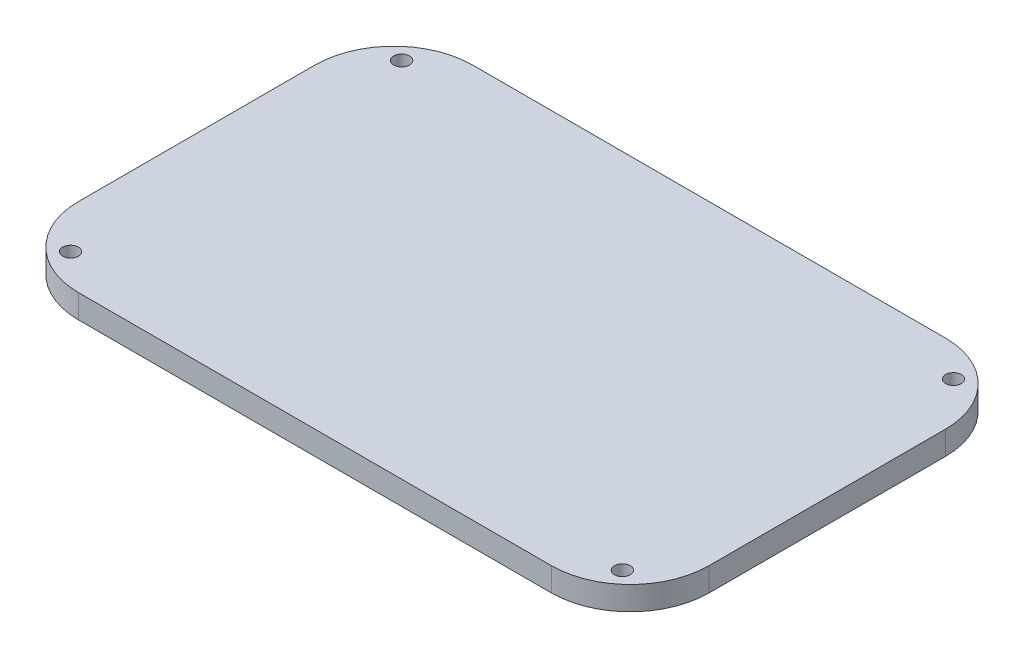
SolidWorks part; units mm, degrees
ref_plane "Front Plane" through (0, 0, 0) normal (0, 0, 1) x (1, 0, 0)
ref_plane "Top Plane" through (0, 0, 0) normal (0, 1, 0) x (1, 0, 0)
ref_plane "Right Plane" through (0, 0, 0) normal (1, 0, 0) x (0, 0, -1)
sketch "Sketch1" plane through (0, 0, 0) normal (0, 1, 0) x (1, 0, 0)
  line L1 (40, 25) -> (-40, 25)
  line L2 (40, 25) -> (40, -25)
  line L3 (40, -25) -> (-40, -25)
  line L4 (-40, 25) -> (-40, -25)
  line L5 (40, 25) -> (-40, -25) construction
  line L6 (40, -25) -> (-40, 25) construction
  point P0 (0, 0)
  dimension "D1" = 80
  dimension "D2" = 50
extrude "Boss-Extrude1" add sketch "Sketch1" along normal blind 3
fillet "Fillet1" radius 10 4 edges at (-40, 1.5, -25) (40, 1.5, -25) (40, 1.5, 25) (-40, 1.5, 25)
sketch "Sketch2" plane through (0, 3, 0) normal (0, 1, 0) x (1, 0, 0)
  line L0 (0, -55) -> (0, 55) construction
  line L1 (-55, 0) -> (55, 0) construction
  circle A0 centre (-35, 21) radius 1
  circle A1 centre (35, 21) radius 1
  circle A2 centre (35, -21) radius 1
  circle A3 centre (-35, -21) radius 1
  dimension "D3" = 2
  dimension "D1" = 35
  dimension "D2" = 21
extrude "Cut-Extrude1" cut sketch "Sketch2" against normal blind 5
